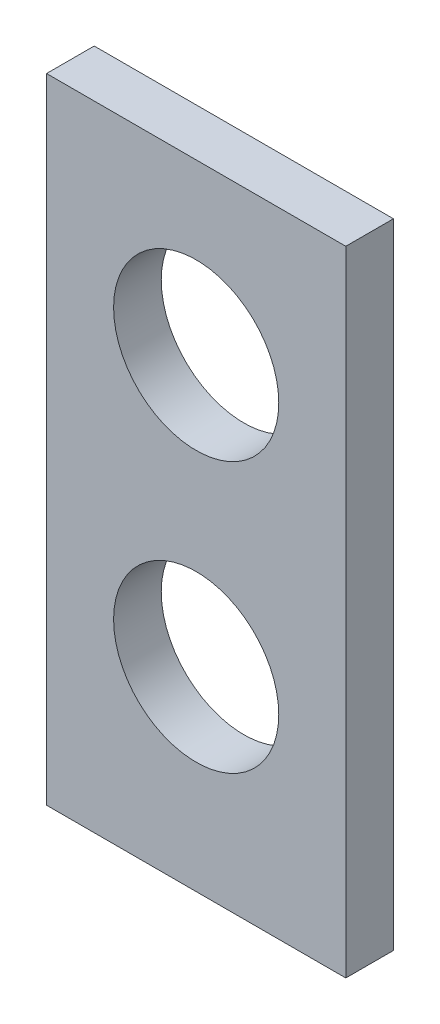
SolidWorks part; units mm, degrees
ref_plane "Front Plane" through (0, 0, 0) normal (0, 0, 1) x (1, 0, 0)
ref_plane "Top Plane" through (0, 0, 0) normal (0, 1, 0) x (1, 0, 0)
ref_plane "Right Plane" through (0, 0, 0) normal (1, 0, 0) x (0, 0, -1)
sketch "Sketch1" plane through (0, 0, 0) normal (0, 0, 1) x (1, 0, 0)
  line L0 (47.1019, 99.7516) -> (-47.1019, -99.7516) construction
  line L1 (-47.1019, 99.7516) -> (47.1019, 99.7516)
  line L2 (-47.1019, 99.7516) -> (-47.1019, -99.7516)
  line L3 (-47.1019, -99.7516) -> (47.1019, -99.7516)
  line L4 (47.1019, 99.7516) -> (47.1019, -99.7516)
  circle A0 centre (0, 46.5177) radius 26
  circle A1 centre (0, -38.4823) radius 26
  point P8 (0, 0)
  dimension "D1" = 52
  dimension "D2" = 52
  dimension "D3" = 85
extrude "Boss-Extrude1" add sketch "Sketch1" along normal blind 15
